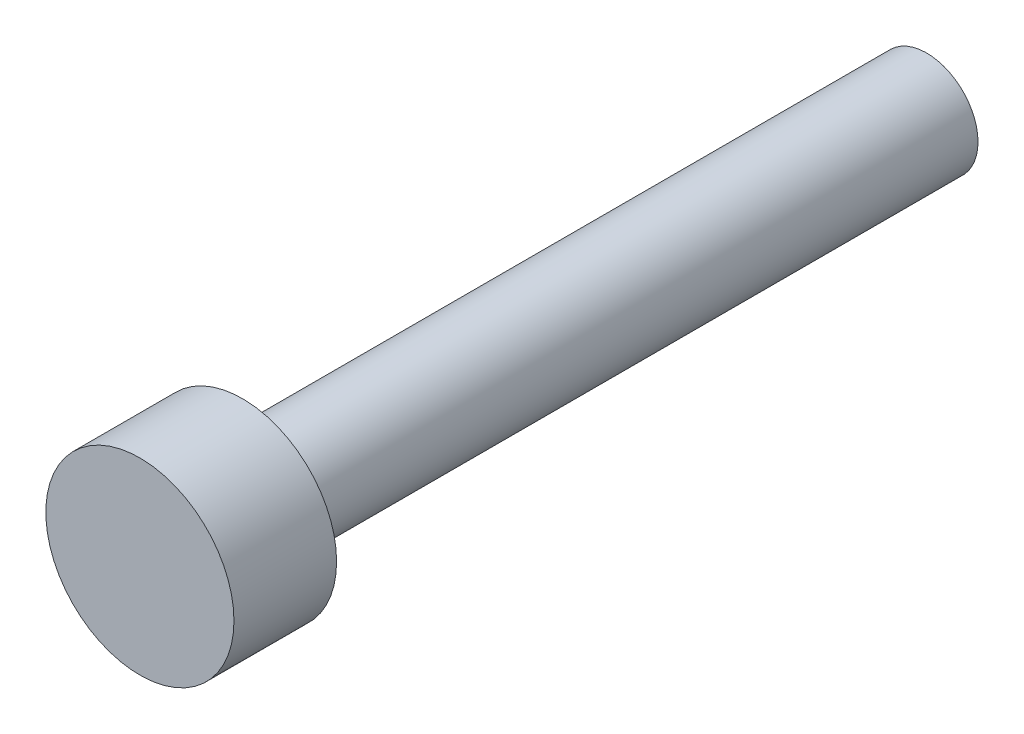
SolidWorks part; units mm, degrees
ref_plane "Front Plane" through (0, 0, 0) normal (0, 0, 1) x (1, 0, 0)
ref_plane "Top Plane" through (0, 0, 0) normal (0, 1, 0) x (1, 0, 0)
ref_plane "Right Plane" through (0, 0, 0) normal (1, 0, 0) x (0, 0, -1)
sketch "Shank_nominal_thread_envelope_profile" plane through (0, 0, 0) normal (0, 0, 1) x (1, 0, 0)
  circle A0 centre (0, 0) radius 1.5
  dimension "D1" = 3
extrude "Shank_nominal_thread_envelope" add sketch "Shank_nominal_thread_envelope_profile" along normal blind 20 from offset 20
sketch "Socket_head_envelope_profile" plane through (0, 0, 0) normal (0, 0, 1) x (1, 0, 0)
  circle A0 centre (0, 0) radius 2.75
  dimension "D1" = 5.5
extrude "Socket_head_envelope" add sketch "Socket_head_envelope_profile" along normal blind 3
